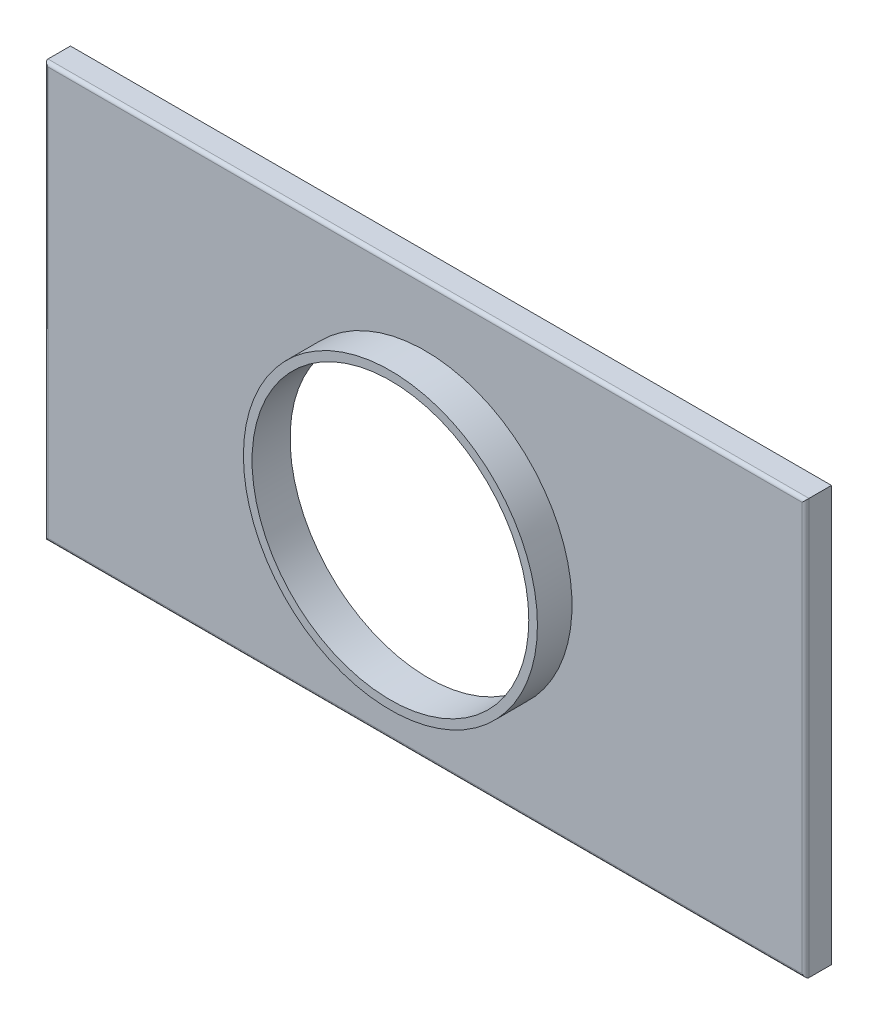
SolidWorks part; units mm, degrees
ref_plane "Front Plane" through (0, 0, 0) normal (0, 0, 1) x (1, 0, 0)
ref_plane "Top Plane" through (0, 0, 0) normal (0, 1, 0) x (1, 0, 0)
ref_plane "Right Plane" through (0, 0, 0) normal (1, 0, 0) x (0, 0, -1)
sketch "Sketch1" plane through (0, 0, 0) normal (0, 0, 1) x (1, 0, 0)
  line L1 (-279.4, -152.4) -> (279.4, -152.4)
  line L2 (-279.4, -152.4) -> (-279.4, 152.4)
  line L3 (-279.4, 152.4) -> (279.4, 152.4)
  line L4 (279.4, -152.4) -> (279.4, 152.4)
  line L5 (-279.4, -152.4) -> (279.4, 152.4) construction
  line L6 (-279.4, 152.4) -> (279.4, -152.4) construction
  point P0 (0, 0)
  dimension "D1" = 304.8
  dimension "D2" = 558.8
extrude "Boss-Extrude1" add sketch "Sketch1" along normal blind 2.54
sketch "Sketch2" plane through (0, 0, 2.54) normal (0, 0, 1) x (1, 0, 0)
  line L0 (276.86, 149.86) -> (-276.86, 149.86)
  line L1 (-276.86, 149.86) -> (-276.86, -149.86)
  line L2 (-276.86, -149.86) -> (276.86, -149.86)
  line L3 (276.86, -149.86) -> (276.86, 149.86)
  line L4 (279.4, -152.4) -> (279.4, 152.4)
  line L5 (279.4, 152.4) -> (-279.4, 152.4)
  line L6 (-279.4, 152.4) -> (-279.4, -152.4)
  line L7 (-279.4, -152.4) -> (279.4, -152.4)
  line L8 (279.4, -152.4) -> (279.4, 152.4)
  line L9 (279.4, 152.4) -> (-279.4, 152.4)
  line L10 (-279.4, 152.4) -> (-279.4, -152.4)
  line L11 (-279.4, -152.4) -> (279.4, -152.4)
  dimension "D1" = 0
  dimension "D2" = 2.54
extrude "Boss-Extrude2" add sketch "Sketch2" against normal blind 19.05
fillet "Fillet1" radius 2.54 4 edges at (0, -152.4, 2.54) (-279.4, 0, 2.54) (0, 152.4, 2.54) (279.4, 0, 2.54)
sketch "Sketch4" plane through (0, 0, 2.54) normal (0, 0, 1) x (1, 0, 0)
  circle A0 centre (0, 0) radius 101.6
  dimension "D1" = 203.2
extrude "Cut-Extrude2" cut sketch "Sketch4" against normal blind 19.05
sketch "Sketch5" plane through (0, 0, 2.54) normal (0, 0, 1) x (1, 0, 0)
  circle A0 centre (0, 0) radius 101.6
  circle A1 centre (0, 0) radius 107.95
  dimension "D1" = 215.9
extrude "Boss-Extrude3" add sketch "Sketch5" along normal blind 25.4
